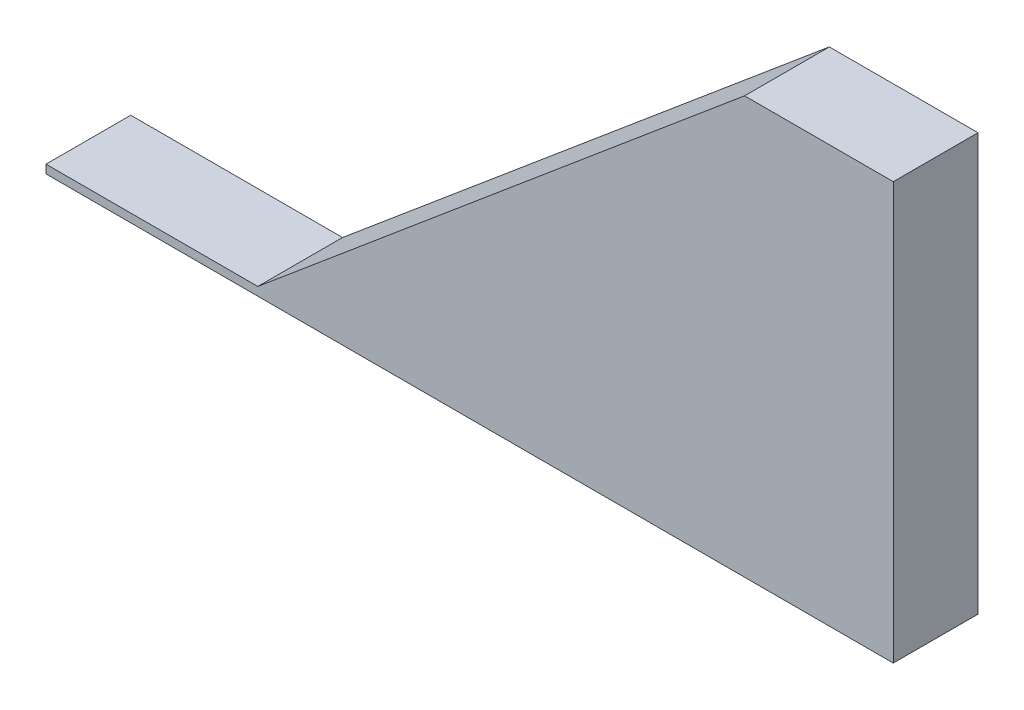
SolidWorks part; units mm, degrees
ref_plane "前视基准面" through (0, 0, 0) normal (0, 0, 1) x (1, 0, 0)
ref_plane "上视基准面" through (0, 0, 0) normal (0, 1, 0) x (1, 0, 0)
ref_plane "右视基准面" through (0, 0, 0) normal (1, 0, 0) x (0, 0, -1)
sketch "草图1" plane through (0, 0, 0) normal (0, 0, 1) x (1, 0, 0)
  line L1 (318.3065, 196.4327) -> (1467.3732, 1160.6141)
  line L2 (-181.6935, 176.4327) -> (1818.3065, 176.4327)
  line L3 (-181.6935, 176.4327) -> (-181.6935, 196.4327)
  line L4 (-181.6935, 196.4327) -> (318.3065, 196.4327)
  line L5 (1818.3065, 176.4327) -> (1818.3065, 196.4327)
  line L6 (1467.3732, 1160.6141) -> (1818.3065, 1160.6141)
  line L7 (1818.3065, 1160.6141) -> (1818.3065, 196.4327)
extrude "凸台-拉伸1" add sketch "草图1" along normal blind 200 contours L7 L5 L2 L3 L4 L1 L6
